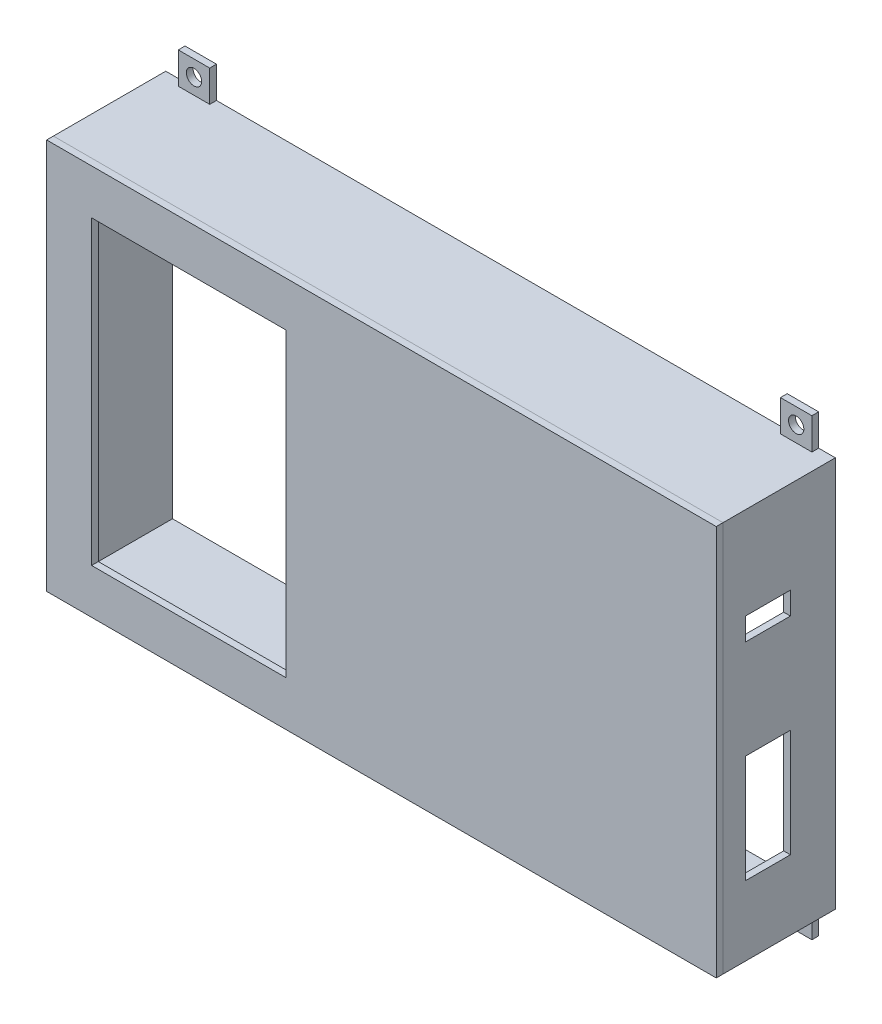
SolidWorks part; units mm, degrees
ref_plane "Front Plane" through (0, 0, 0) normal (0, 0, 1) x (1, 0, 0)
ref_plane "Top Plane" through (0, 0, 0) normal (0, 1, 0) x (1, 0, 0)
ref_plane "Right Plane" through (0, 0, 0) normal (1, 0, 0) x (0, 0, -1)
sketch "Sketch1" plane through (0, 0, 0) normal (0, 0, 1) x (1, 0, 0)
  line L0 (0, 104.6975) -> (0, 2.54) construction
  line L1 (63.7875, 26.6188) -> (145.7875, 26.6188) construction
  line L2 (145.7875, 26.6188) -> (145.7875, 80.6188) construction
  line L3 (145.7875, 80.6188) -> (63.7875, 80.6188) construction
  line L4 (63.7875, 94.6188) -> (9.7875, 94.6188) construction
  line L5 (9.7875, 94.6188) -> (9.7875, 12.6188) construction
  line L6 (9.7875, 12.6188) -> (63.7875, 12.6188) construction
  line L7 (63.7875, 12.6188) -> (63.7875, 94.6188) construction
  line L9 (63.7875, 26.6188) -> (145.7875, 26.6188)
  line L10 (145.7875, 26.6188) -> (145.7875, 80.6188)
  line L11 (145.7875, 80.6188) -> (63.7875, 80.6188)
  line L12 (63.7875, 94.6188) -> (9.7875, 94.6188)
  line L13 (9.7875, 94.6188) -> (9.7875, 12.6188)
  line L14 (9.7875, 12.6188) -> (63.7875, 12.6188)
  line L15 (63.7875, 12.6188) -> (63.7875, 26.6188)
  line L16 (63.7875, 80.6188) -> (63.7875, 94.6188)
  line L27 (66.2875, 10.1188) -> (66.2875, 11.6188)
  line L41 (4.5, 95.6188) -> (4.5, 11.6188)
  line L42 (4.5, 11.6188) -> (150.5, 11.6188)
  line L43 (150.5, 95.6188) -> (150.5, 11.6188)
  line L44 (4.5, 95.6188) -> (150.5, 95.6188)
  line L49 (3, 97.1188) -> (152, 97.1188)
  line L50 (3, 97.1188) -> (3, 10.1188)
  line L51 (3, 10.1188) -> (152, 10.1188)
  line L52 (152, 97.1188) -> (152, 10.1188)
  line L57 (0, 2.54) -> (155.575, 2.54) construction
  dimension "D3" = 149
  dimension "D4" = 87
  dimension "D5" = 3
  dimension "D6" = 7.5788
  dimension "D1" = 1.5
extrude "Boss-Extrude1" add sketch "Sketch1" along normal blind 25
sketch "Sketch2" plane through (0, 0, 25) normal (0, 0, 1) x (1, 0, 0)
  line L0 (56.2875, 87.1188) -> (56.2875, 20.1188)
  line L1 (63.7875, 12.6188) -> (63.7875, 94.6188) construction
  line L6 (142, 20.1188) -> (142, 87.1188)
  line L12 (142, 87.1188) -> (13, 87.1188)
  line L14 (56.2875, 87.1188) -> (13, 87.1188)
  line L16 (13, 87.1188) -> (13, 20.1188)
  line L17 (13, 87.1188) -> (13, 20.1188)
  line L18 (13, 20.1188) -> (142, 20.1188)
  line L19 (13, 20.1188) -> (56.2875, 20.1188)
  point P2 (56.2875, 87.1188)
  point P4 (56.2875, 20.1188)
  point P7 (56.2875, 21.5521)
  point P8 (57.2594, 87.1188)
  point P10 (56.2875, 21.6188)
  point P12 (56.2875, 85.6188)
  point P13 (56.2875, 87.1188)
  point P15 (56.2875, 20.1188)
  dimension "D2" = 7.5
  dimension "D1" = 10
extrude "Boss-Extrude2" add sketch "Sketch2" along normal blind 1.5 separate body
sketch "Sketch3" plane through (0, 0, 0) normal (0, 0, 1) x (1, 0, 0)
  line L1 (7.2875, 97.1188) -> (14.2875, 97.1188)
  line L2 (7.2875, 97.1188) -> (7.2875, 104.1188)
  line L3 (7.2875, 104.1188) -> (14.2875, 104.1188)
  line L4 (14.2875, 97.1188) -> (14.2875, 104.1188)
  line L5 (7.2875, 10.1188) -> (14.2875, 10.1188)
  line L6 (7.2875, 10.1188) -> (7.2875, 3.1188)
  line L7 (7.2875, 3.1188) -> (14.2875, 3.1188)
  line L8 (14.2875, 10.1188) -> (14.2875, 3.1188)
  line L19 (7.2875, 10.1188) -> (148.2875, 10.1188) construction
  line L20 (148.2875, 10.1188) -> (141.2875, 10.1188)
  line L21 (148.2875, 10.1188) -> (148.2875, 3.1188)
  line L22 (148.2875, 3.1188) -> (141.2875, 3.1188)
  line L23 (141.2875, 10.1188) -> (141.2875, 3.1188)
  line L24 (148.2875, 10.1188) -> (148.2875, 97.1188) construction
  line L25 (7.2875, 53.6188) -> (148.2875, 53.6188) construction
  line L26 (7.2875, 97.1188) -> (7.2875, 10.1188) construction
  line L27 (148.2875, 104.1188) -> (141.2875, 104.1188)
  line L28 (141.2875, 97.1188) -> (141.2875, 104.1188)
  line L29 (148.2875, 97.1188) -> (141.2875, 97.1188)
  line L30 (148.2875, 97.1188) -> (148.2875, 104.1188)
  point P26 (10.7875, 100.6188)
  point P30 (10.7875, 104.1188)
  point P31 (7.2875, 100.6188)
  point P32 (10.7875, 6.6188)
  point P33 (7.2875, 6.6188)
  point P34 (10.7875, 3.1188)
  point P35 (144.7875, 6.6188)
  point P36 (0, 0)
  point P37 (144.7875, 3.1188)
  point P38 (141.2875, 6.6188)
  point P39 (0, 0)
  point P40 (144.7875, 100.6188)
  dimension "D2" = 7
extrude "Boss-Extrude3" add sketch "Sketch3" along normal blind 1.5
hole_wizard "M3 Clearance Hole1" positions "Sketch7" profile "Sketch5" hole size "M3" standard "ANSI Metric" end condition through all
sketch "Sketch7" plane through (0, 0, 1.5) normal (0, 0, 1) x (1, 0, 0)
  point P0 (10.7875, 6.6188)
  point P3 (10.7875, 100.6188)
  point P13 (144.7875, 6.6188)
  point P16 (144.7875, 100.6188)
  point P20 (0, 0)
  point P21 (0, 0)
sketch "Sketch5" plane through (10.7875, 6.6188, 1.5) normal (1, 0, 0) x (0, -1, 0)
  line L0 (0, 0) -> (0, 1.5)
  line L1 (0, 1.5) -> (1.7, 1.5)
  line L2 (1.7, 1.5) -> (1.7, 0)
  line L5 (1.7, 0) -> (0, 0)
  line L11 (0, -6.35) -> (0, 107.95) construction
  dimension "Thru Hole Dia." = 3.4
  dimension "Thru Hole Depth" = 1.5
sketch "Sketch9" plane through (152, 0, 0) normal (1, 0, 0) x (0, 0, -1)
  line L1 (-20, 25.6188) -> (-10, 25.6188)
  line L2 (-20, 25.6188) -> (-20, 49.6188)
  line L3 (-20, 49.6188) -> (-10, 49.6188)
  line L4 (-10, 25.6188) -> (-10, 49.6188)
  line L5 (0, 2.54) -> (0, 104.6975) construction
  line L6 (-25, 11.6188) -> (0, 11.6188) construction
  line L7 (-25, 11.6188) -> (0, 11.6188)
  line L9 (-10, 71.6188) -> (-20, 71.6188)
  line L10 (-10, 71.6188) -> (-10, 76.6188)
  line L11 (-10, 76.6188) -> (-20, 76.6188)
  line L12 (-20, 71.6188) -> (-20, 76.6188)
  dimension "D1" = 10
  dimension "D2" = 10
  dimension "D3" = 14
  dimension "D4" = 38
  dimension "D5" = 60
  dimension "D6" = 65
extrude "Cut-Extrude1" cut sketch "Sketch9" against normal up to surface (1.5 mm away) contours L1 L4 L3 L2 | L12 L9 L10 L11 up to face at (150.5, 53.6188, 12.5)
